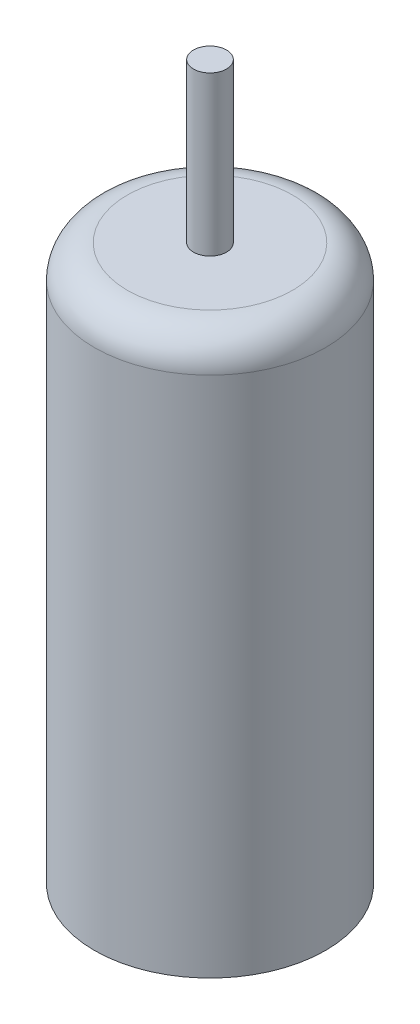
SolidWorks part; units mm, degrees
ref_plane "Front Plane" through (0, 0, 0) normal (0, 0, 1) x (1, 0, 0)
ref_plane "Top Plane" through (0, 0, 0) normal (0, 1, 0) x (1, 0, 0)
ref_plane "Right Plane" through (0, 0, 0) normal (1, 0, 0) x (0, 0, -1)
sketch "Sketch1" plane through (0, 0, 0) normal (0, 1, 0) x (1, 0, 0)
  circle A0 centre (0, 0) radius 3.5
extrude "Boss-Extrude1" add sketch "Sketch1" along normal blind 16.8
sketch "Sketch2" plane through (0, 16.8, 0) normal (0, 1, 0) x (1, 0, 0)
  circle A0 centre (0, 0) radius 0.5
extrude "Boss-Extrude2" add sketch "Sketch2" along normal blind 4.8
fillet "Fillet1" radius 1 1 edges at (0, 16.8, 3.5)
